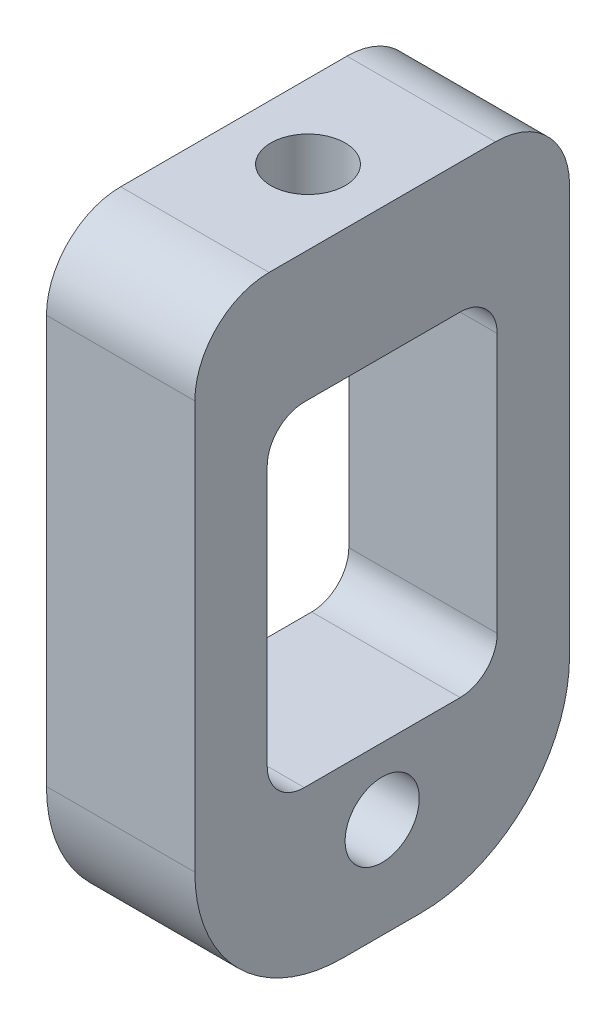
SolidWorks part; units mm, degrees
other "Markup1"
sketch "Sketch6" plane through (-4, 8, -3.5) normal (-0.1216, 0.9914, -0.0475) x (-0.0131, 0.0463, 0.9988)
sketch "Sketch19" plane through (-2.475, 25, -7.5) normal (-0.1216, 0.9914, -0.0475) x (-0.0131, 0.0463, 0.9988)
sketch "Sketch20" plane through (-2.475, 25, -7.5) normal (-0.1216, 0.9914, -0.0475) x (-0.0131, 0.0463, 0.9988)
sketch "Sketch25" plane through (-2, 25, -5.05) normal (-0.1216, 0.9914, -0.0475) x (-0.0131, 0.0463, 0.9988)
sketch "Sketch26" plane through (-2, 25, -5.05) normal (-0.1216, 0.9914, -0.0475) x (-0.0131, 0.0463, 0.9988)
sketch "Sketch27" [suppressed] plane through (-2.475, 25, -7.5) normal (-0.1216, 0.9914, -0.0475) x (-0.0131, 0.0463, 0.9988)
sketch "Sketch28" plane through (-2.475, 25, -7.5) normal (-0.1216, 0.9914, -0.0475) x (-0.0131, 0.0463, 0.9988)
material "7075 T651 protolabs"
ref_plane "Front Plane" through (0, 0, 0) normal (0, 0, 1) x (1, 0, 0)
ref_plane "Top Plane" through (0, 0, 0) normal (0, 1, 0) x (1, 0, 0)
ref_plane "Right Plane" through (0, 0, 0) normal (1, 0, 0) x (0, 0, -1)
sketch "Sketch16" plane through (0, 0, 0) normal (0, 1, 0) x (1, 0, 0)
  line L1 (-2.475, -7.5) -> (2.475, -7.5)
  line L2 (-2.475, -7.5) -> (-2.475, 7.5)
  line L3 (-2.475, 7.5) -> (2.475, 7.5)
  line L4 (2.475, -7.5) -> (2.475, 7.5)
  line L5 (-2.475, -7.5) -> (2.475, 7.5) construction
  line L6 (-2.475, 7.5) -> (2.475, -7.5) construction
  point P0 (0, 0)
  dimension "D1" = 15
  dimension "D2" = 4.95
extrude "Main Extrude_Locking" [suppressed] add sketch "Sketch16" along normal blind 25
sketch "Sketch18" [suppressed] plane through (-2.475, 0, 0) normal (-1, 0, 0) x (0, 0, 1)
  line L0 (0, 0) -> (0, 2.5) construction
  line L1 (-7.5, 0) -> (7.5, 0) construction
  circle A0 centre (0, 3.7) radius 1.2
  dimension "D2" = 2.4
  dimension "D1" = 2.5
extrude "Cut-Extrude1" [suppressed] cut sketch "Sketch18" against normal up to surface (4.95 mm away)
sketch "Sketch8" [suppressed] plane through (-2.475, 0, 0) normal (-1, 0, 0) x (0, 0, 1)
  line L0 (0, 4.9) -> (-7.5, 4.9) construction
  line L1 (-7.5, 25) -> (-7.5, 0) construction
  line L3 (5, 5.9) -> (-5, 5.9)
  line L4 (5, 5.9) -> (5, 18.9)
  line L5 (5, 18.9) -> (-5, 18.9)
  line L6 (-5, 5.9) -> (-5, 18.9)
  line L7 (5, 5.9) -> (-5, 18.9) construction
  line L8 (5, 18.9) -> (-5, 5.9) construction
  circle A0 centre (0, 3.7) radius 1.2 construction
  point P6 (0, 12.4)
  dimension "D1" = 2
  dimension "D2" = 13
  dimension "D3" = 10
extrude "Cut-Extrude2" [suppressed] cut sketch "Sketch8" against normal up to surface (4.95 mm away)
sketch "Sketch9" [suppressed] plane through (0, 25, 0) normal (0, 1, 0) x (1, 0, 0)
  circle A0 centre (0, 0) radius 1.35
  dimension "D1" = 2.7
extrude "Cut-Extrude3" [suppressed] cut sketch "Sketch9" against normal up to surface (6.1 mm away)
fillet "Fillet1" [suppressed] radius 5
fillet "Fillet2" [suppressed] radius 3
fillet "Fillet3" [suppressed] radius 0.5
sketch "Sketch21" plane through (0, 0, 0) normal (0, 1, 0) x (1, 0, 0)
  line L1 (-2, -5.05) -> (2, -5.05)
  line L2 (-2, -5.05) -> (-2, 5.05)
  line L3 (-2, 5.05) -> (2, 5.05)
  line L4 (2, -5.05) -> (2, 5.05)
  line L5 (-2, -5.05) -> (2, 5.05) construction
  line L6 (-2, 5.05) -> (2, -5.05) construction
  point P0 (0, 0)
  dimension "D1" = 4
  dimension "D2" = 10.1
extrude "Boss-Extrude1" add sketch "Sketch21" along normal blind 17
sketch "Sketch22" plane through (-2, 0, 0) normal (-1, 0, 0) x (0, 0, 1)
  line L0 (-5.05, 0) -> (5.05, 0) construction
  circle A0 centre (0, 2.7) radius 1
  point P4 (0, 0)
  dimension "D1" = 2
  dimension "D2" = 2.7
extrude "Cut-Extrude4" cut sketch "Sketch22" against normal up to surface (4 mm away) up to face at (2, 8.5, 0)
sketch "Sketch23" plane through (-2, 0, 0) normal (-1, 0, 0) x (0, 0, 1)
  line L0 (-5.05, 0) -> (5.05, 0) construction
  line L1 (3.1, 4.5) -> (-3.1, 4.5)
  line L2 (3.1, 4.5) -> (3.1, 13.5)
  line L3 (3.1, 13.5) -> (-3.1, 13.5)
  line L4 (-3.1, 4.5) -> (-3.1, 13.5)
  line L5 (-5.05, 17) -> (5.05, 17) construction
  point P8 (0, 4.5)
  dimension "D1" = 4.5
  dimension "D2" = 3.5
  dimension "D3" = 6.2
extrude "Cut-Extrude5" cut sketch "Sketch23" against normal up to surface (4 mm away) up to face at (2, 2.7, 1)
sketch "Sketch24" plane through (0, 17, 0) normal (0, 1, 0) x (1, 0, 0)
  circle A0 centre (0, 0) radius 1
  dimension "D1" = 2
extrude "Cut-Extrude6" cut sketch "Sketch24" against normal up to surface (3.5 mm away) up to face at (0, 13.5, 0)
fillet "Fillet4" radius 4 2 edges at (0, 0, 5.05) (0, 0, -5.05)
fillet "Fillet5" radius 2 2 edges at (0, 17, -5.05) (0, 17, 5.05)
fillet "Fillet6" radius 1 4 edges at (0, 4.5, 3.1) (0, 4.5, -3.1) (0, 13.5, -3.1) (0, 13.5, 3.1)
